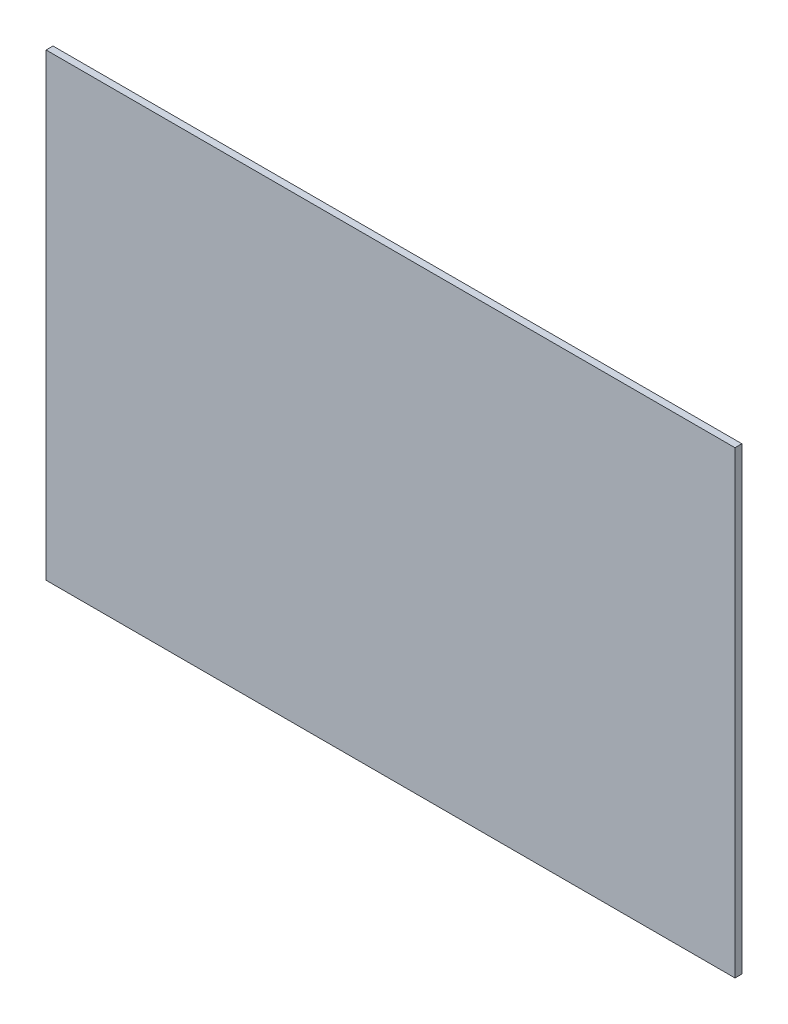
SolidWorks part; units mm, degrees
ref_plane "Alzado" through (0, 0, 0) normal (0, 0, 1) x (1, 0, 0)
ref_plane "Planta" through (0, 0, 0) normal (0, 1, 0) x (1, 0, 0)
ref_plane "Vista lateral" through (0, 0, 0) normal (1, 0, 0) x (0, 0, -1)
sketch "Croquis1" plane through (0, 0, 0) normal (0, 0, 1) x (1, 0, 0)
  line L1 (-150, 100) -> (150, 100)
  line L2 (-150, 100) -> (-150, -100)
  line L3 (-150, -100) -> (150, -100)
  line L4 (150, 100) -> (150, -100)
  line L5 (-150, 100) -> (150, -100) construction
  line L6 (-150, -100) -> (150, 100) construction
  point P0 (0, 0)
  dimension "D1" = 200
  dimension "D2" = 300
extrude "Saliente-Extruir1" add sketch "Croquis1" along normal blind 3
